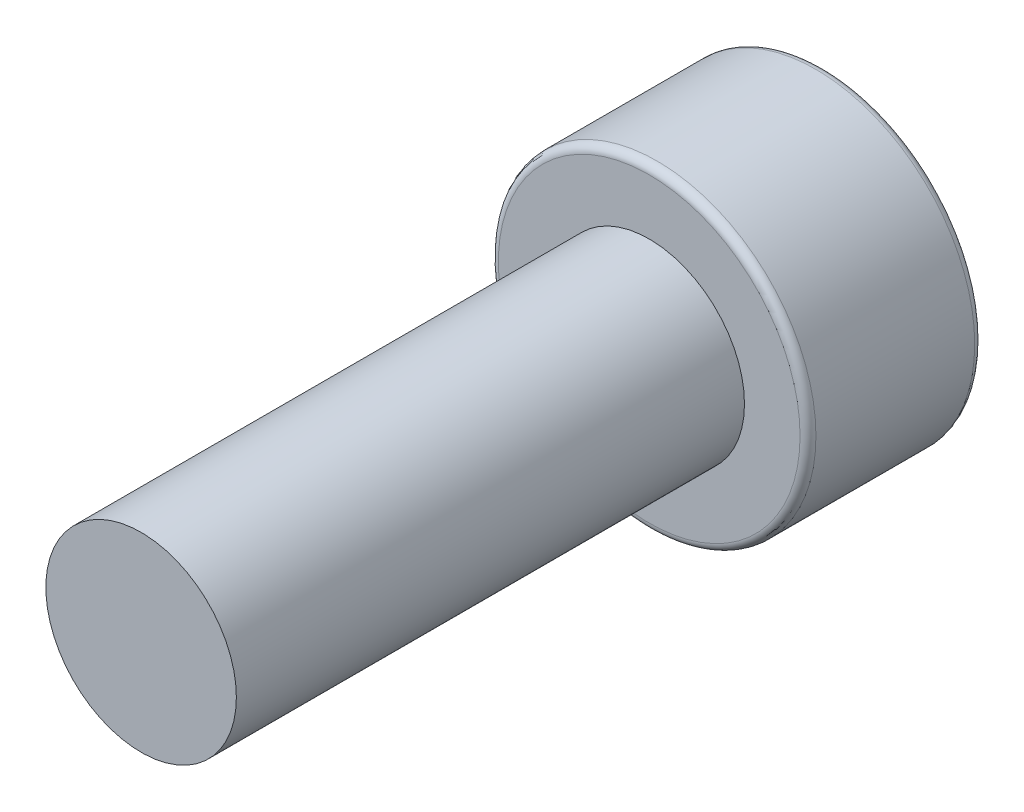
SolidWorks part; units mm, degrees
ref_plane "Front Plane" through (0, 0, 0) normal (0, 0, 1) x (1, 0, 0)
ref_plane "Top Plane" through (0, 0, 0) normal (0, 1, 0) x (1, 0, 0)
ref_plane "Right Plane" through (0, 0, 0) normal (1, 0, 0) x (0, 0, -1)
sketch "Sketch1" plane through (0, 0, 0) normal (0, 0, 1) x (1, 0, 0)
  circle A0 centre (0, 0) radius 2.5
  dimension "D1" = 5
extrude "Boss-Extrude1" add sketch "Sketch1" along normal blind 2.75
sketch "Sketch2" plane through (0, 0, 2.75) normal (0, 0, 1) x (1, 0, 0)
  circle A0 centre (0, 0) radius 1.5
  dimension "D1" = 3
extrude "Boss-Extrude2" add sketch "Sketch2" along normal blind 8
sketch "Sketch3" plane through (0, 0, 0) normal (0, 0, -1) x (-1, 0, 0)
  line L1 (1.4434, 0) -> (0.7217, 1.25)
  line L2 (0.7217, 1.25) -> (-0.7217, 1.25)
  line L3 (-0.7217, 1.25) -> (-1.4434, 0)
  line L4 (-1.4434, 0) -> (-0.7217, -1.25)
  line L5 (-0.7217, -1.25) -> (0.7217, -1.25)
  line L6 (0.7217, -1.25) -> (1.4434, 0)
  circle A0 centre (0, 0) radius 1.25 construction
  dimension "D1" = 2.5
extrude "Cut-Extrude1" cut sketch "Sketch3" against normal blind 2
chamfer "Chamfer1" distance 0.25 angle 45 6 edges at (-1.0825, -0.625, 2) (0, -1.25, 2) (1.0825, -0.625, 2) (1.0825, 0.625, 2) (0, 1.25, 2) (-1.0825, 0.625, 2)
fillet "Fillet1" radius 0.125 8 edges at (0, 1.25, 0) (1.0825, 0.625, 0) (1.0825, -0.625, 0) (0, -1.25, 0) (-1.0825, -0.625, 0) (-1.0825, 0.625, 0) (2.5, 0, 0) (2.5, 0, 2.75)
